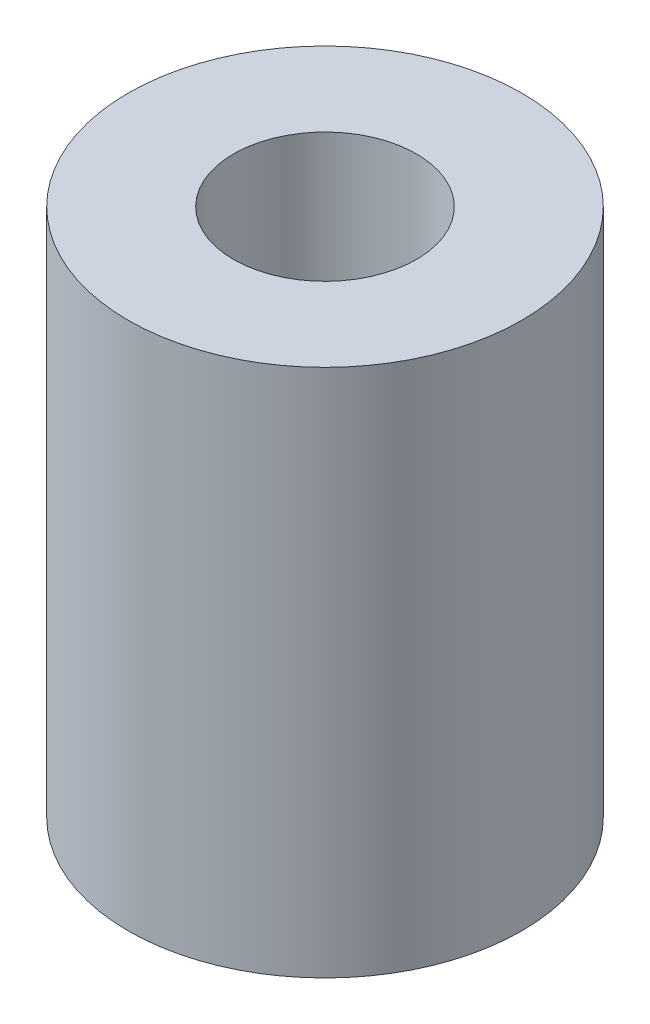
SolidWorks part; units mm, degrees
ref_plane "Front Plane" through (0, 0, 0) normal (0, 0, 1) x (1, 0, 0)
ref_plane "Top Plane" through (0, 0, 0) normal (0, 1, 0) x (1, 0, 0)
ref_plane "Right Plane" through (0, 0, 0) normal (1, 0, 0) x (0, 0, -1)
sketch "Sketch1" plane through (0, 0, 0) normal (0, 1, 0) x (1, 0, 0)
  circle A0 centre (0, 0) radius 2.363
  circle A1 centre (0, 0) radius 1.0983
  dimension "D1" = 4.726
extrude "Boss-Extrude1" add sketch "Sketch1" along normal blind 6.35
